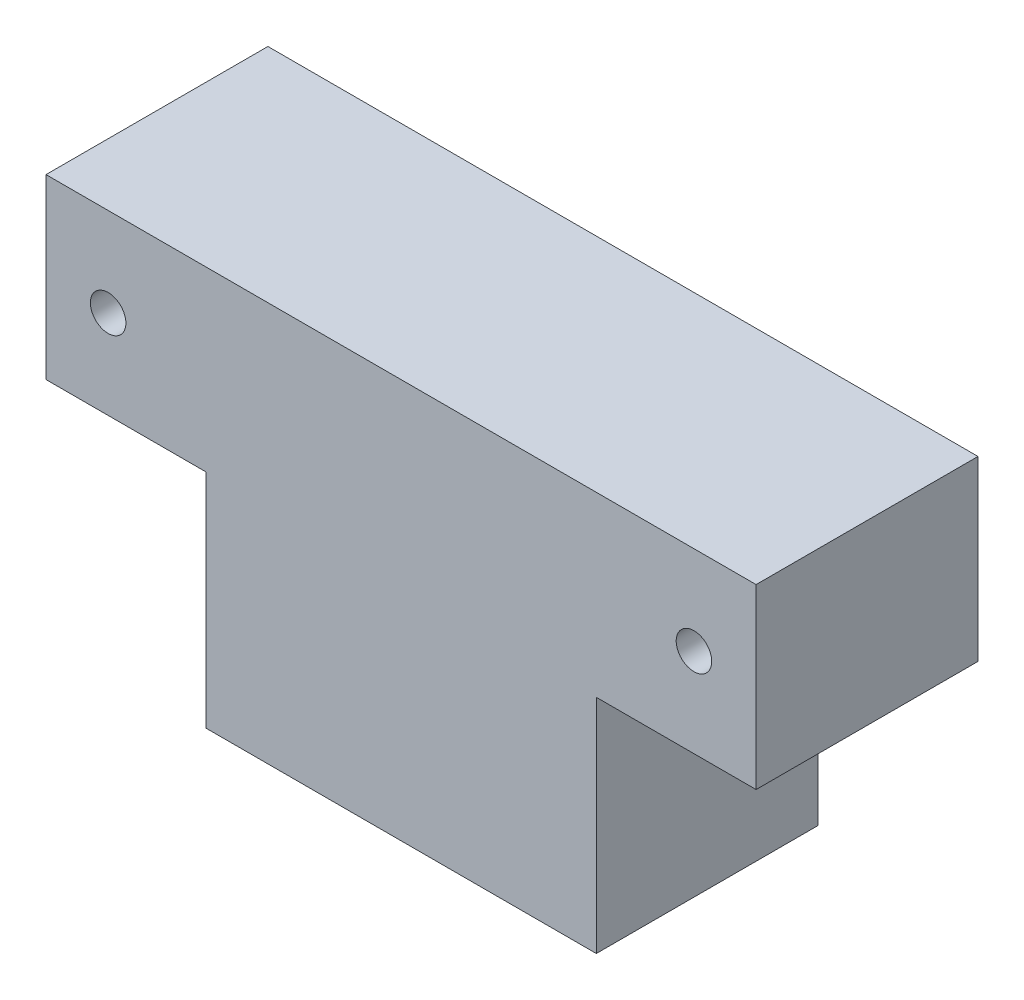
SolidWorks part; units mm, degrees
ref_plane "Ön Düzlem" through (0, 0, 0) normal (0, 0, 1) x (1, 0, 0)
ref_plane "Üst Düzlem" through (0, 0, 0) normal (0, 1, 0) x (1, 0, 0)
ref_plane "Sağ Düzlem" through (0, 0, 0) normal (1, 0, 0) x (0, 0, -1)
sketch "Çizim1" plane through (0, 0, 0) normal (0, 0, 1) x (1, 0, 0)
  line L0 (-22, -10) -> (-40, -10)
  line L1 (40, -10) -> (22, -10)
  line L2 (40, -10) -> (40, 10)
  line L3 (40, 10) -> (-40, 10)
  line L4 (-40, -10) -> (-40, 10)
  line L5 (40, -10) -> (-40, 10) construction
  line L6 (40, 10) -> (-40, -10) construction
  line L8 (-22, -10) -> (-22, -35)
  line L9 (-22, -35) -> (22, -35)
  line L10 (22, -10) -> (22, -35)
  circle A0 centre (33, 0) radius 2
  circle A1 centre (-33, 0) radius 2
  point P0 (0, 0)
  dimension "D7" = 4
  dimension "D8" = 4
  dimension "D9" = 7
  dimension "D10" = 7
  dimension "D11" = 10
  dimension "D12" = 10
  dimension "D1" = 20
  dimension "D2" = 80
  dimension "D3" = 25
  dimension "D4" = 18
  dimension "D5" = 18
extrude "Yükseklik-Ekstrüzyon1" add sketch "Çizim1" along normal blind 25
